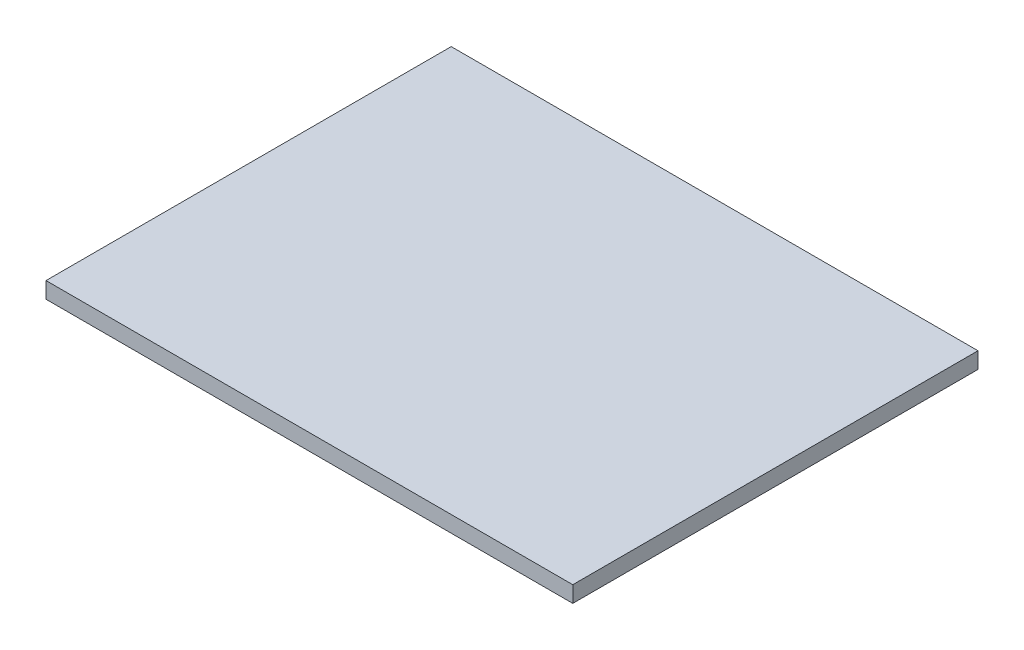
SolidWorks part; units mm, degrees
ref_plane "Front Plane" through (0, 0, 0) normal (0, 0, 1) x (1, 0, 0)
ref_plane "Top Plane" through (0, 0, 0) normal (0, 1, 0) x (1, 0, 0)
ref_plane "Right Plane" through (0, 0, 0) normal (1, 0, 0) x (0, 0, -1)
sketch "Sketch1" plane through (0, 0, 0) normal (0, 1, 0) x (1, 0, 0)
  line L5 (-162.5, 125) -> (162.5, 125)
  line L6 (-162.5, 125) -> (-162.5, -125)
  line L7 (-162.5, -125) -> (162.5, -125)
  line L8 (162.5, 125) -> (162.5, -125)
  line L9 (-162.5, 125) -> (162.5, -125) construction
  line L10 (-162.5, -125) -> (162.5, 125) construction
  point P0 (0, 0)
  dimension "D1" = 325
  dimension "D2" = 250
extrude "Boss-Extrude1" add sketch "Sketch1" along normal blind 10
